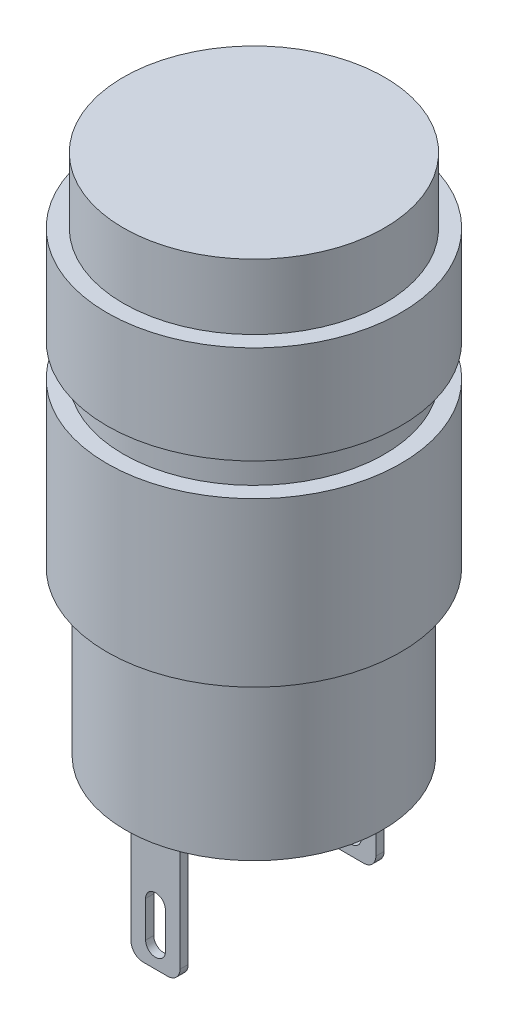
SolidWorks part; units mm, degrees
ref_plane "Front Plane" through (0, 0, 0) normal (0, 0, 1) x (1, 0, 0)
ref_plane "Top Plane" through (0, 0, 0) normal (0, 1, 0) x (1, 0, 0)
ref_plane "Right Plane" through (0, 0, 0) normal (1, 0, 0) x (0, 0, -1)
sketch "Sketch2" plane through (0, 0, 0) normal (0, 1, 0) x (1, 0, 0)
  circle A0 centre (0, 0) radius 7.875
extrude "Boss-Extrude1" add sketch "Sketch2" along normal blind 22
sketch "Sketch4" plane through (0, 0, 0) normal (0, 1, 0) x (1, 0, 0)
  circle A0 centre (0, 0) radius 9
extrude "Boss-Extrude2" add sketch "Sketch4" along normal blind 6 from surface at 22 starting at face at (0, 22, 7.875)
sketch "Sketch5" plane through (0, 0, 0) normal (0, 1, 0) x (1, 0, 0)
  circle A0 centre (0, 0) radius 8
extrude "Boss-Extrude3" add sketch "Sketch5" along normal blind 4 from surface at 28 starting at face at (0, 28, 9)
sketch "Sketch6" plane through (0, 0, 0) normal (0, 1, 0) x (1, 0, 0)
  line L0 (-1.1895, -5.841) -> (1.8105, -6.341) construction
  line L1 (-1.1895, 5.659) -> (1.8105, 5.659)
  line L2 (-1.1895, 5.659) -> (-1.1895, 6.159)
  line L3 (-1.1895, 6.159) -> (1.8105, 6.159)
  line L4 (1.8105, 5.659) -> (1.8105, 6.159)
  line L5 (-1.1895, 5.659) -> (1.8105, 6.159) construction
  line L6 (-1.1895, 6.159) -> (1.8105, 5.659) construction
  line L7 (-1.1895, -5.841) -> (1.8105, -5.841)
  line L8 (-1.1895, -6.341) -> (-1.1895, -5.841)
  line L9 (1.8105, -6.341) -> (1.8105, -5.841)
  line L10 (-1.1895, -6.341) -> (1.8105, -6.341)
  line L11 (-1.1895, -6.341) -> (1.8105, -5.841) construction
  point P0 (0.3105, 5.909)
  point P5 (0.3105, -6.091)
extrude "Boss-Extrude4" add sketch "Sketch6" against normal blind 8
fillet "Fillet2" radius 0.75 4 edges at (-1.1895, -8, 6.091) (1.8105, -8, 6.091) (-1.1895, -8, -5.909) (1.8105, -8, -5.909)
ref_plane "Plane1" through (0, 0, -6.159) normal (0, 0, 1) x (1, 0, 0)
sketch "Sketch7" plane through (0, 0, -6.159) normal (0, 0, 1) x (1, 0, 0)
  line L0 (0.3105, -8) -> (0.3105, 0) construction
  line L1 (1.0605, -8) -> (-0.4395, -8) construction
  line L2 (1.8105, 0) -> (-1.1895, 0) construction
  line L3 (0.3105, -6.7602) -> (0.3105, -4.5479) construction
  line L4 (-0.2964, -6.7602) -> (-0.2964, -4.5479)
  line L5 (0.9173, -6.7602) -> (0.9173, -4.5479)
  arc A0 (-0.2964, -6.7602) -> (0.9173, -6.7602) centre (0.3105, -6.7602) ccw
  arc A1 (0.9173, -4.5479) -> (-0.2964, -4.5479) centre (0.3105, -4.5479) ccw
  point P8 (0.3105, -5.654)
extrude "Cut-Extrude1" cut sketch "Sketch7" along normal through all
sketch "Sketch11" plane through (0, 0, 0) normal (0, 1, 0) x (1, 0, 0)
  circle A0 centre (0, 0) radius 9
  circle A1 centre (0, 0) radius 8
extrude "Boss-Extrude5" add sketch "Sketch11" along normal blind 10 from offset 10 separate body
